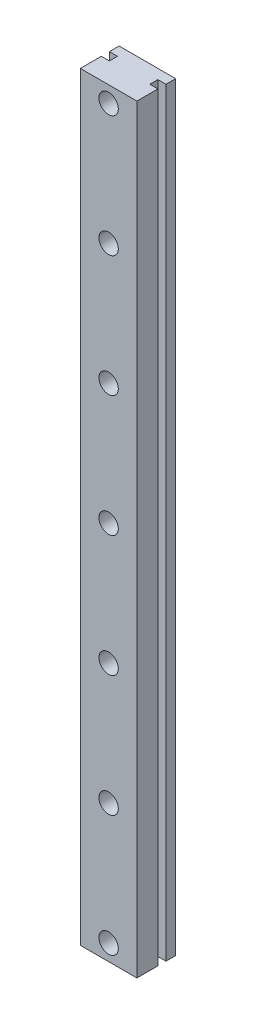
SolidWorks part; units mm, degrees
ref_plane "前视基准面" through (0, 0, 0) normal (0, 0, 1) x (1, 0, 0)
ref_plane "上视基准面" through (0, 0, 0) normal (0, 1, 0) x (1, 0, 0)
ref_plane "右视基准面" through (0, 0, 0) normal (1, 0, 0) x (0, 0, -1)
sketch "草图1" plane through (0, 0, 0) normal (0, 1, 0) x (1, 0, 0)
  line L0 (0, 0) -> (0, 2.6)
  line L1 (0, 2.6) -> (1, 2.6)
  line L2 (1, 2.6) -> (1, 3.6)
  line L3 (1, 3.6) -> (0, 3.6)
  line L4 (0, 3.6) -> (0, 4.8)
  line L5 (0, 4.8) -> (7, 4.8)
  line L6 (0, 0) -> (7, 0)
  line L7 (3.5, 4.8) -> (3.5, -2.1169) construction
  line L8 (7, 3.6) -> (7, 4.8)
  line L9 (6, 3.6) -> (7, 3.6)
  line L10 (6, 2.6) -> (6, 3.6)
  line L11 (7, 2.6) -> (6, 2.6)
  line L12 (7, 0) -> (7, 2.6)
  point P11 (3.5, 0)
  dimension "D1" = 4.8
  dimension "D2" = 7
  dimension "D3" = 1
  dimension "D4" = 1.2
  dimension "D5" = 1
extrude "凸台-拉伸1" add sketch "草图1" along normal blind 94
sketch "草图2" plane through (0, 0, -4.8) normal (0, 0, -1) x (-1, 0, 0)
  line L0 (-7, 0) -> (0, 0) construction
  line L1 (-3.5, 0) -> (-3.5, 187.5272) construction
  line L2 (-7, 47) -> (28.6734, 47) construction
  line L3 (-7, 94) -> (-7, 0) construction
  line L4 (-7, 94) -> (0, 94) construction
  circle A5 centre (-3.5, 62) radius 1.2
  circle A6 centre (-3.5, 77) radius 1.2
  circle A7 centre (-3.5, 47) radius 1.2
  circle A9 centre (-3.5, 32) radius 1.2
  circle A10 centre (-3.5, 17) radius 1.2
  circle A12 centre (-3.5, 92) radius 1.2 [skipped]
  circle A13 centre (-3.5, 2) radius 1.2 [skipped]
  circle A14 centre (-3.5, 92) radius 1.2
  circle A15 centre (-3.5, 2) radius 1.2
  dimension "D1" = 2.4
  dimension "D2" = 4
  dimension "D3" = 4
  dimension "D4" = 15
  dimension "D5" = 15
  dimension "D6" = 47
  dimension "D7" = 94
extrude "切除-拉伸1" cut sketch "草图2" against normal through all
